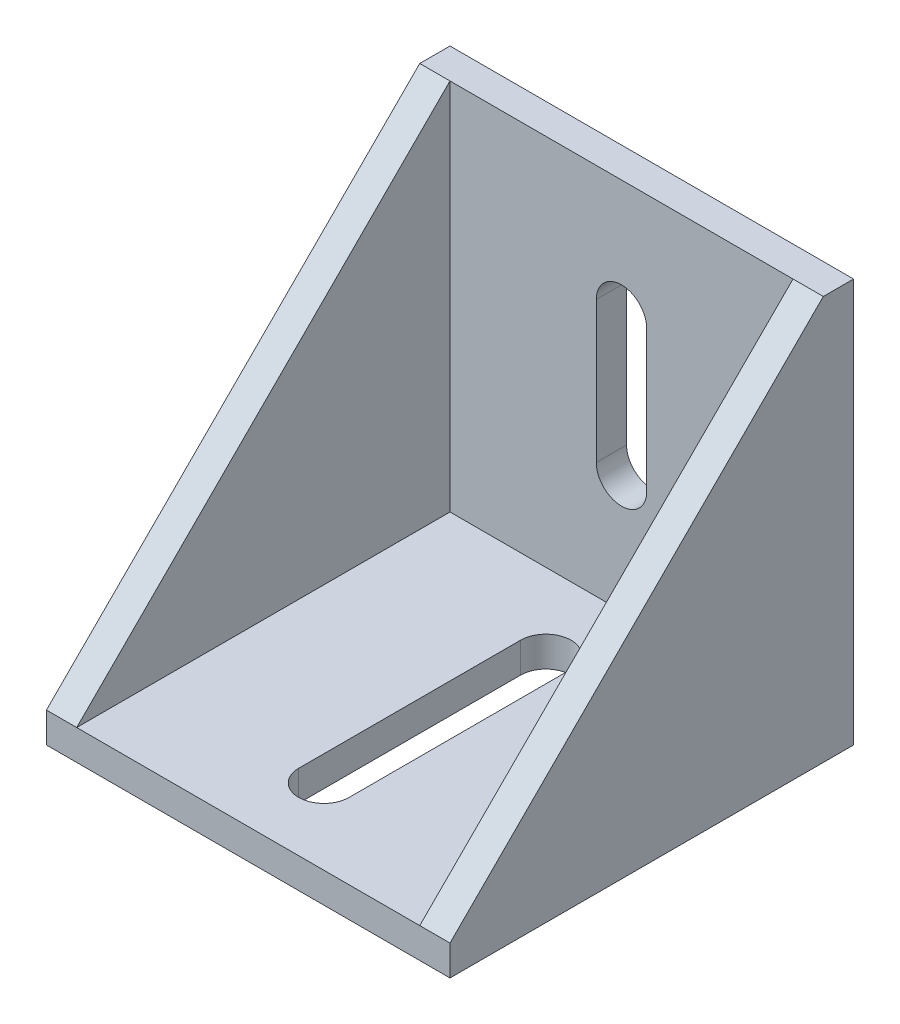
SolidWorks part; units mm, degrees
material "1060 Alloy"
ref_plane "Front Plane" through (0, 0, 0) normal (0, 0, 1) x (1, 0, 0)
ref_plane "Top Plane" through (0, 0, 0) normal (0, 1, 0) x (1, 0, 0)
ref_plane "Right Plane" through (0, 0, 0) normal (1, 0, 0) x (0, 0, -1)
sketch "Sketch1" plane through (0, 0, 0) normal (0, 1, 0) x (1, 0, 0)
  line L0 (0, 0) -> (40, 0)
  line L1 (40, 0) -> (40, -40)
  line L2 (40, -40) -> (0, -40)
  line L3 (0, -40) -> (0, 0)
  dimension "D1" = 40
  dimension "D2" = 40
extrude "Boss-Extrude1" add sketch "Sketch1" along normal blind 3
sketch "Sketch2" plane through (0, 0, 0) normal (0, 0, -1) x (-1, 0, 0)
  line L0 (-40, 3) -> (-40, 40)
  line L1 (-40, 40) -> (0, 40)
  line L2 (0, 40) -> (0, 3)
  line L3 (-40, 3) -> (0, 3) construction
  line L4 (0, 3) -> (-40, 3)
  dimension "D1" = 37
extrude "Boss-Extrude2" add sketch "Sketch2" against normal blind 3
sketch "Sketch3" plane through (0, 0, 0) normal (-1, 0, 0) x (0, 0, 1)
  line L0 (3, 3) -> (40, 3) construction
  line L1 (3, 40) -> (3, 3)
  line L2 (3, 3) -> (40, 3)
  line L3 (3, 40) -> (40, 3)
extrude "Boss-Extrude3" add sketch "Sketch3" against normal blind 3
sketch "Sketch4" plane through (40, 0, 0) normal (1, 0, 0) x (0, 0, -1)
  line L0 (-3, 40) -> (-3, 3) construction
  line L1 (-40, 3) -> (-3, 3) construction
  line L2 (-40, 3) -> (-3, 3)
  line L3 (-3, 3) -> (-3, 40)
  line L4 (-3, 40) -> (-40, 3)
  dimension "D1" = 37
extrude "Boss-Extrude4" add sketch "Sketch4" against normal blind 3
sketch "Sketch5" plane through (0, 0, 3) normal (0, 0, 1) x (1, 0, 0)
  line L0 (20, 40) -> (20, 3) construction
  line L1 (3, 40) -> (37, 40) construction
  line L2 (37, 3) -> (3, 3) construction
  line L3 (3, 21.5) -> (37, 21.5) construction
  line L4 (3, 40) -> (3, 3) construction
  line L5 (37, 3) -> (37, 40) construction
  line L6 (20, 14.5) -> (20, 28.5) construction
  line L7 (17.5, 14.5) -> (17.5, 28.5)
  line L8 (22.5, 14.5) -> (22.5, 28.5)
  arc A0 (17.5, 14.5) -> (22.5, 14.5) centre (20, 14.5) ccw
  arc A1 (22.5, 28.5) -> (17.5, 28.5) centre (20, 28.5) ccw
  point P14 (20, 21.5)
extrude "Cut-Extrude1" cut sketch "Sketch5" against normal blind 3
sketch "Sketch6" plane through (0, 3, 0) normal (0, 1, 0) x (1, 0, 0)
  line L0 (3, -21.5) -> (37, -21.5) construction
  line L3 (3, -3) -> (3, -40) construction
  line L6 (37, -40) -> (37, -3) construction
  line L7 (20, -3) -> (20, -40) construction
  line L8 (37, -3) -> (3, -3) construction
  line L9 (3, -40) -> (37, -40) construction
  line L10 (20, -32.5) -> (20, -10.5) construction
  line L12 (17.5, -32.5) -> (17.5, -10.5)
  line L13 (22.5, -32.5) -> (22.5, -10.5)
  arc A0 (17.5, -32.5) -> (22.5, -32.5) centre (20, -32.5) ccw
  arc A1 (22.5, -10.5) -> (17.5, -10.5) centre (20, -10.5) ccw
  point P16 (20, -21.5)
extrude "Cut-Extrude2" cut sketch "Sketch6" against normal blind 3
